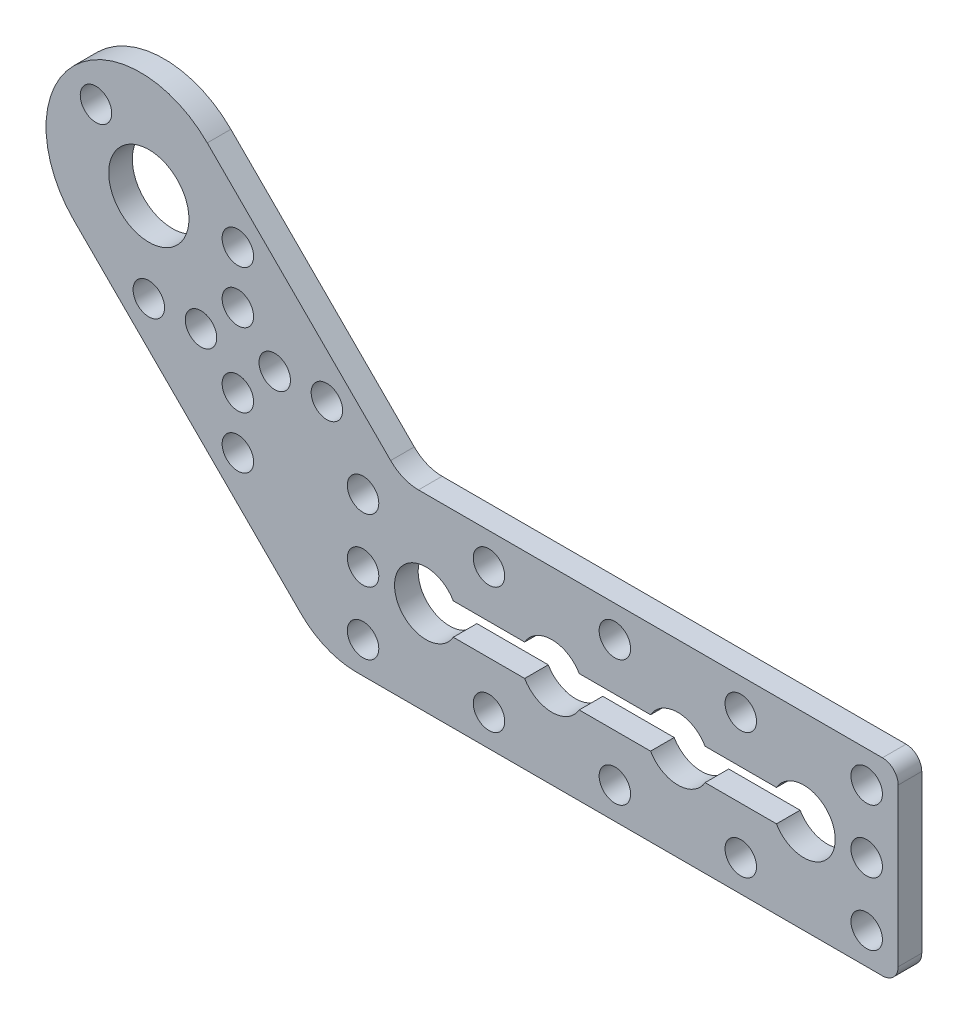
SolidWorks part; units mm, degrees
ref_plane "前视基准面" through (0, 0, 0) normal (0, 0, 1) x (1, 0, 0)
ref_plane "上视基准面" through (0, 0, 0) normal (0, 1, 0) x (1, 0, 0)
ref_plane "右视基准面" through (0, 0, 0) normal (1, 0, 0) x (0, 0, -1)
sketch "草图1" plane through (0, 0, 0) normal (0, 0, 1) x (1, 0, 0)
  line L0 (0, 0) -> (35.0294, 0)
  line L1 (-9.9411, -24) -> (0, 0)
  line L2 (35.0294, -24) -> (-9.9411, -24)
  line L3 (-9.9411, -24) -> (-38.2254, 4.2843) construction
  line L4 (35.0294, -12) -> (-4.9706, -12) construction
  line L5 (-21.2548, 21.2548) -> (0, 0) construction
  arc A0 (-21.2548, 21.2548) -> (-38.2254, 4.2843) centre (-29.7401, 12.7696) ccw construction
  arc A1 (35.0294, -24) -> (35.0294, 0) centre (35.0294, -12) ccw
  circle A2 centre (35.0294, -12) radius 4
  dimension "D6" = 8
  dimension "D1" = 135
  dimension "D2" = 40
  dimension "D3" = 40
  dimension "D4" = 24
  dimension "D5" = 24
extrude "凸台-拉伸1" add sketch "草图1" along normal blind 3
sketch "草图2" plane through (0, 0, 3) normal (0, 0, 1) x (1, 0, 0)
  line L0 (35.0294, -12) -> (43.0294, -12) construction
  circle A0 centre (43.0294, -12) radius 2
  dimension "D1" = 4
  dimension "D2" = 8
extrude "切除-拉伸1" cut sketch "草图2" against normal blind 3
pattern_circular "阵列(圆周)1" count 8 over 360 about axis through (35.0294, -12, 0) along (0, 0, 1) of "切除-拉伸1"
sketch "草图3" plane through (0, 0, 3) normal (0, 0, 1) x (1, 0, 0)
  line L0 (19.0294, -4) -> (35.0294, -4) construction
  line L1 (19.0294, -20) -> (35.0294, -20) construction
  line L2 (19.0294, -20) -> (19.0294, -4) construction
  circle A0 centre (19.0294, -4) radius 2
  circle A1 centre (19.0294, -20) radius 2
  circle A2 centre (19.0294, -12) radius 2
  dimension "D2" = 4
  dimension "D1" = 16
extrude "切除-拉伸2" cut sketch "草图3" against normal blind 3
pattern_linear "阵列(线性)1" count 3 spacing 8 along (-1, 0, 0) of "切除-拉伸2"
sketch "草图4" plane through (0, 0, 3) normal (0, 0, 1) x (1, 0, 0)
  line L0 (27.0294, -4) -> (35.0294, -4) construction
  line L1 (27.0294, -20) -> (35.0294, -20) construction
  circle A0 centre (27.0294, -4) radius 2
  circle A1 centre (27.0294, -20) radius 2
  circle A2 centre (29.3726, -17.6569) radius 2 construction
  dimension "D1" = 8
sketch "草图8" plane through (0, 0, 3) normal (0, 0, 1) x (1, 0, 0)
  line L0 (19.0294, -10) -> (-7.5153, -10)
  line L1 (19.0294, -14) -> (-11.2342, -14)
  line L2 (-11.2342, -14) -> (-7.5153, -10)
  circle A0 centre (19.0294, -12) radius 2 construction
  circle A1 centre (3.0294, -12) radius 2 construction
  arc A2 (19.0294, -14) -> (19.0294, -10) centre (19.0294, -12) ccw
sketch "草图14" plane through (0, 0, 3) normal (0, 0, 1) x (1, 0, 0)
  line L0 (3.0294, -10) -> (19.0294, -10)
  line L1 (3.0294, -14) -> (19.0294, -14)
  line L2 (19.0294, -14) -> (19.0294, -10)
  line L3 (3.0294, -10) -> (3.0294, -14)
  circle A0 centre (3.0294, -12) radius 2 construction
  circle A1 centre (19.0294, -12) radius 2 construction
extrude "切除-拉伸6" cut sketch "草图14" against normal blind 3
sketch "草图16" plane through (0, 0, 3) normal (0, 0, 1) x (1, 0, 0)
  line L0 (-4.9706, -20) -> (3.0294, -20) construction
  circle A0 centre (-4.9706, -20) radius 2
  circle A1 centre (3.0294, -20) radius 2 construction
  dimension "D1" = 8
extrude "切除-拉伸7" [suppressed] cut sketch "草图16" against normal blind 3
sketch "草图31" plane through (0, 0, 3) normal (0, 0, 1) x (1, 0, 0)
  line L0 (7.7157, -8.6863) -> (19.0294, -20) construction
  line L1 (-9.9411, -24) -> (35.0294, -24) construction
  line L2 (35.0294, -12) -> (-9.2377, -12) construction
  circle A0 centre (7.7157, -8.6863) radius 2
  circle A1 centre (11.0294, -4) radius 2 construction
  dimension "D1" = 16
  dimension "D2" = 45
extrude "切除-拉伸9" [suppressed] cut sketch "草图31" against normal blind 3
sketch "草图33" plane through (0, 0, 3) normal (0, 0, 1) x (1, 0, 0)
  line L0 (7.7157, -15.3137) -> (19.0294, -4) construction
  line L1 (-9.9411, -24) -> (35.0294, -24) construction
  circle A0 centre (7.7157, -15.3137) radius 2
  circle A1 centre (3.0294, -20) radius 2 construction
  dimension "D1" = 45
  dimension "D2" = 16
extrude "切除-拉伸11" [suppressed] cut sketch "草图33" against normal blind 3 contours A0
fillet "圆角6" [suppressed] radius 0.2
sketch "草图36" plane through (0, 0, 3) normal (0, 0, 1) x (1, 0, 0)
  line L0 (0.6837, -6.3405) -> (-10.63, 4.9732) construction
  line L1 (35.0294, 0) -> (0, 0) construction
  line L2 (0, 0) -> (-12.775, 12.775) construction
  line L3 (11.0294, -4) -> (-1.6569, -4) construction
  circle A0 centre (0.6837, -6.3405) radius 2
  circle A1 centre (3.0294, -4) radius 2 construction
  dimension "D2" = 4
  dimension "D1" = 135
  dimension "D3" = 12.69
  dimension "D4" = 16
extrude "切除-拉伸12" [suppressed] cut sketch "草图36" against normal blind 3
fillet "圆角8" [suppressed] radius 0.2
sketch "草图39" plane through (0, 0, 3) normal (0, 0, 1) x (1, 0, 0)
  line L0 (7.7157, -8.6863) -> (19.0294, -20) construction
  line L1 (-9.9411, -24) -> (35.0294, -24) construction
  circle A0 centre (7.7157, -8.6863) radius 2
  circle A1 centre (11.0294, -4) radius 2 construction
  dimension "D2" = 16
  dimension "D1" = 45
extrude "切除-拉伸13" [suppressed] cut sketch "草图39" against normal blind 25.4
sketch "草图40" plane through (0, 0, 3) normal (0, 0, 1) x (1, 0, 0)
  line L0 (7.7157, -15.3137) -> (19.0294, -4) construction
  line L1 (-9.9411, -24) -> (35.0294, -24) construction
  circle A0 centre (7.7157, -15.3137) radius 2
  circle A1 centre (3.0294, -20) radius 2 construction
  dimension "D1" = 45
  dimension "D2" = 16
extrude "切除-拉伸14" [suppressed] cut sketch "草图40" against normal blind 25.4
fillet "圆角9" [suppressed] radius 0.2
sketch "草图42" plane through (0, 0, 3) normal (0, 0, 1) x (1, 0, 0)
  line L0 (-0.2843, -8.6863) -> (11.0294, -20) construction
  line L1 (-9.9411, -24) -> (35.0294, -24) construction
  line L2 (-0.2843, -15.3137) -> (11.0294, -4) construction
  circle A0 centre (-0.2843, -8.6863) radius 2
  circle A1 centre (3.0294, -4) radius 2 construction
  circle A3 centre (-0.2843, -15.3137) radius 2
  dimension "D1" = 45
  dimension "D2" = 16
  dimension "D3" = 45
  dimension "D4" = 16
extrude "切除-拉伸15" [suppressed] cut sketch "草图42" against normal blind 25.4
sketch "草图43" [suppressed] plane through (0, 0, 3) normal (0, 0, 1) x (1, 0, 0)
  line L0 (-1.6985, -10.1005) -> (0.201, -12)
  line L1 (3.2579, -11.178) -> (4.1469, -10.289)
  line L2 (4.1469, -10.289) -> (1.1299, -7.2721)
  line L3 (-0.2843, -8.6863) -> (11.0294, -20) construction
  line L4 (-0.375, -15.4044) -> (11.0294, -4) construction
  line L5 (-1.6985, -13.8995) -> (1.1299, -16.7279)
  line L6 (1.1299, -16.7279) -> (5.0318, -12.8261)
  line L7 (5.0318, -12.8261) -> (3.2579, -11.178)
  line L8 (2.0994, -10.1016) -> (1.6152, -10.5858) construction
  line L9 (35.0294, 0) -> (0, 0) construction
  line L10 (0.201, -12) -> (-1.6985, -13.8995)
  line L11 (-1.6985, -10.1005) -> (1.1299, -7.2721)
  circle A0 centre (-0.2843, -8.6863) radius 2 construction
  circle A1 centre (-0.2843, -15.3137) radius 2 construction
  dimension "D1" = 135
extrude "切除-拉伸17" [suppressed] cut sketch "草图43" against normal blind 25.4
fillet "圆角10" [suppressed] radius 0.5
mirror "镜向2" about plane through (-9.9411, -24, 3) normal (0.9239, -0.3827, 0) of bodies 116 110
fillet "圆角1" radius 5 1 edges at (0, 0, 1.5)
fillet "圆角2" radius 10 1 edges at (-9.9411, -24, 1.5)
sketch "草图11" plane through (0, 0, 3) normal (0, 0, 1) x (1, 0, 0)
  line L0 (0, 0) -> (-9.6258, -23.2388) construction
  line L1 (3.0294, -12) -> (-4.9706, -12) construction
  arc A0 (-12.8701, -21.0711) -> (-5.799, -24) centre (-5.799, -14) ccw construction
sketch "草图13" plane through (0, 0, 3) normal (0, 0, 1) x (1, 0, 0)
  circle A0 centre (-4.9706, -12) radius 2
  circle A1 centre (3.0294, -12) radius 2 construction
extrude "切除-拉伸5" cut sketch "草图13" against normal blind 3
sketch "草图44" plane through (0, 0, 3) normal (0, 0, 1) x (1, 0, 0)
  line L0 (35.0294, 0) -> (2.0711, 0) construction
  line L1 (23.7346, 0) -> (71.0294, 0)
  line L2 (23.7346, 0) -> (23.7346, -24)
  line L3 (23.7346, -24) -> (71.0294, -24)
  line L4 (71.0294, 0) -> (71.0294, -24)
  line L5 (-5.799, -24) -> (35.0294, -24) construction
  line L6 (43.0294, -12) -> (71.0294, -12) construction
  dimension "D1" = 28
extrude "凸台-拉伸2" add sketch "草图44" against normal up to surface (3 mm away) up to face at (-2.9706, -12, 0)
sketch "草图45" plane through (0, 0, 3) normal (0, 0, 1) x (1, 0, 0)
  line L0 (67.0294, -4) -> (19.0294, -4) construction
  line L1 (71.0294, -24) -> (71.0294, 0) construction
  circle A0 centre (67.0294, -4) radius 2
  circle A1 centre (67.0294, -20) radius 2
  dimension "D1" = 4
  dimension "D2" = 16
  dimension "D3" = 4
extrude "切除-拉伸18" cut sketch "草图45" against normal blind 10
pattern_linear "阵列(线性)2" count 6 spacing 8 along (-1, 0, 0) of "切除-拉伸18"
sketch "草图47" plane through (0, 0, 3) normal (0, 0, 1) x (1, 0, 0)
  line L0 (67.0294, -12) -> (67.0294, -20) construction
  line L1 (67.0294, -12) -> (19.0294, -12) construction
  line L2 (59.0294, -10) -> (35.0294, -10)
  line L3 (19.0294, -10) -> (3.0294, -10) construction
  line L4 (17.0627, -10) -> (17.0627, -14)
  line L5 (3.0294, -14) -> (19.0294, -14) construction
  line L6 (35.0294, -14) -> (59.0294, -14)
  line L8 (35.0294, -12) -> (35.0294, -4) construction
  line L9 (27.0294, -12) -> (27.0294, -4) construction
  line L10 (17.0627, -10) -> (27.0294, -10)
  line L11 (17.0627, -14) -> (27.0294, -14)
  line L12 (59.0294, -10) -> (59.0294, -4) construction
  circle A0 centre (67.0294, -12) radius 2
  circle A2 centre (67.0294, -4) radius 2 construction
  arc A3 (35.0294, -10) -> (35.0294, -14) centre (35.0294, -12) ccw
  arc A4 (27.0294, -14) -> (27.0294, -10) centre (27.0294, -12) ccw
  circle A5 centre (27.0294, -4) radius 2 construction
  arc A6 (59.0294, -14) -> (59.0294, -10) centre (59.0294, -12) ccw
  dimension "D1" = 2
  dimension "D2" = 2
extrude "切除-拉伸19" cut sketch "草图47" against normal blind 10
fillet "圆角11" radius 2 2 edges at (71.0294, -24, 1.5) (71.0294, 0, 1.5)
sketch "草图48" plane through (0, 0, 3) normal (0, 0, 1) x (1, 0, 0)
  line L0 (-10.6274, -17.6569) -> (-16.2843, -12) construction
  line L1 (-12.8701, -21.0711) -> (-41.7401, 7.799) construction
  line L2 (-4.9706, -20) -> (3.0294, -20) construction
  circle A0 centre (-4.9706, -20) radius 2
  circle A1 centre (3.0294, -20) radius 2 construction
  circle A2 centre (-10.6274, -17.6569) radius 2
  dimension "D1" = 8
  dimension "D2" = 8
extrude "切除-拉伸20" cut sketch "草图48" against normal blind 10
sketch "草图49" plane through (0, 0, 3) normal (0, 0, 1) x (1, 0, 0)
  line L0 (-33.7407, 2.2965) -> (-11.1397, -21.4851)
  line L1 (-11.1397, -21.4851) -> (-6.8616, -17.4194)
  line L2 (-6.8616, -17.4194) -> (-11.8728, -12.1464)
  line L3 (-11.8728, -12.1464) -> (-1.3201, -0.8589)
  line L4 (-1.3201, -0.8589) -> (-18.0661, 15.5538)
  line L5 (-18.0661, 15.5538) -> (-33.7407, 2.2965)
extrude "凸台-拉伸3" [suppressed] add sketch "草图49" against normal up to surface (3 mm away)
sketch "草图50" plane through (0, 0, 3) normal (0, 0, 1) x (1, 0, 0)
  line L0 (-25.2548, 0.2843) -> (-25.2548, 16.2843) construction
  line L1 (-25.2548, 16.2843) -> (-17.2548, 8.2843) construction
  line L2 (-24.7696, 24.7696) -> (-1.4645, 1.4645) construction
  line L3 (-17.2548, 8.2843) -> (-17.2548, -7.7157) construction
  line L4 (-17.2548, 8.2843) -> (-9.2548, 0.2843) construction
  line L5 (-9.2548, -15.7157) -> (-9.2548, 0.2843) construction
  circle A0 centre (-25.2548, 0.2843) radius 2
  circle A1 centre (-27.598, 10.6274) radius 2 construction
  circle A2 centre (-17.2548, 8.2843) radius 2
  circle A3 centre (-17.2548, -7.7157) radius 2
  circle A4 centre (-9.2548, 0.2843) radius 2 construction
  circle A5 centre (-9.2548, -15.7157) radius 2 construction
  dimension "D1" = 16
  dimension "D2" = 8
  dimension "D3" = 16
  dimension "D4" = 16
  dimension "D5" = 8
extrude "切除-拉伸21" [suppressed] cut sketch "草图50" against normal blind 10
sketch "草图52" [suppressed] plane through (0, 0, 3) normal (0, 0, 1) x (1, 0, 0)
  line L0 (-16.2843, -0.6863) -> (-27.598, 10.6274) construction
  line L1 (-12.8701, -21.0711) -> (-41.7401, 7.799) construction
  circle A0 centre (-16.2843, -0.6863) radius 2
  circle A1 centre (-17.2548, -7.7157) radius 2 construction
  dimension "D1" = 16
extrude "切除-拉伸22" [suppressed] cut sketch "草图52" against normal blind 10
sketch "草图53" plane through (0, 0, 3) normal (0, 0, 1) x (1, 0, 0)
  line L0 (-4.9706, -4) -> (3.0294, -4) construction
  line L2 (-4.9706, -4) -> (-4.9706, -12) construction
  circle A0 centre (-4.9706, -4) radius 2
  circle A1 centre (3.0294, -4) radius 2 construction
extrude "切除-拉伸23" [suppressed] cut sketch "草图53" against normal blind 10
sketch "草图58" [suppressed] plane through (0, 0, 3) normal (0, 0, 1) x (1, 0, 0)
  line L0 (-12.9706, -12) -> (-4.9706, -12) construction
  circle A0 centre (-12.9706, -12) radius 2
  circle A1 centre (-4.9706, -12) radius 2 construction
  circle A2 centre (-17.2548, -7.7157) radius 2 construction
  circle A3 centre (-12.9706, 4) radius 2
  circle A4 centre (-17.2548, 8.2843) radius 2 construction
  dimension "D1" = 8
  dimension "D2" = 16
extrude "切除-拉伸24" [suppressed] cut sketch "草图58" against normal blind 10
sketch "草图61" [suppressed] plane through (0, 0, 3) normal (0, 0, 1) x (1, 0, 0)
  line L0 (-27.598, 10.6274) -> (-4.9706, -12) construction
  line L1 (-23.3553, 3.5563) -> (-12.0416, -7.7574)
  line L2 (-9.2132, -4.9289) -> (-20.5269, 6.3848)
  arc A0 (-20.5269, 6.3848) -> (-23.3553, 3.5563) centre (-21.9411, 4.9706) ccw
  circle A1 centre (-27.598, 10.6274) radius 2 construction
  arc A2 (-12.0416, -7.7574) -> (-9.2132, -4.9289) centre (-10.6274, -6.3431) ccw
  circle A3 centre (-4.9706, -4) radius 2 construction
  dimension "D1" = 8
  dimension "D2" = 8
extrude "切除-拉伸25" [suppressed] cut sketch "草图61" against normal blind 10
sketch "草图62" plane through (0, 0, 3) normal (0, 0, 1) x (1, 0, 0)
  line L0 (-25.2548, 16.2843) -> (-21.2548, 12.2843) construction
  line L1 (-24.7696, 24.7696) -> (-1.4645, 1.4645) construction
  circle A0 centre (-21.2548, 12.2843) radius 2
  circle A1 centre (-25.2548, 16.2843) radius 2 construction
  circle A2 centre (-21.2548, -3.7157) radius 2
  dimension "D1" = 4
  dimension "D2" = 16
extrude "切除-拉伸26" [suppressed] cut sketch "草图62" against normal blind 10
sketch "草图63" plane through (0, 0, 3) normal (0, 0, 1) x (1, 0, 0)
  circle A0 centre (-4.9706, -0.6863) radius 3.0171
extrude "凸台-拉伸4" [suppressed] add sketch "草图63" against normal up to surface (3 mm away)
sketch "草图64" plane through (0, 0, 3) normal (0, 0, 1) x (1, 0, 0)
  line L0 (-4.9706, -4) -> (3.0294, -4) construction
  circle A0 centre (-4.9706, -4) radius 2
  circle A1 centre (3.0294, -4) radius 2 construction
  dimension "D1" = 8
extrude "切除-拉伸27" [suppressed] cut sketch "草图64" against normal blind 10
sketch "草图65" plane through (0, 0, 3) normal (0, 0, 1) x (1, 0, 0)
  circle A0 centre (-10.6274, -17.6569) radius 3.287
extrude "凸台-拉伸5" [suppressed] add sketch "草图65" against normal up to surface (3 mm away)
sketch "草图66" plane through (0, 0, 3) normal (0, 0, 1) x (1, 0, 0)
  circle A0 centre (-27.3986, 0) radius 3.2271
extrude "凸台-拉伸6" add sketch "草图66" against normal up to surface (3 mm away) up to face at (-8.6274, -17.6569, 0)
sketch "草图67" plane through (0, 0, 3) normal (0, 0, 1) x (1, 0, 0)
  line L0 (-25.2548, 0.2843) -> (-25.2548, 16.2843) construction
  circle A0 centre (-25.2548, 0.2843) radius 2
  circle A1 centre (-25.2548, 16.2843) radius 2 construction
  dimension "D1" = 16
extrude "切除-拉伸28" cut sketch "草图67" against normal blind 10
sketch "草图70" plane through (0, 0, 3) normal (0, 0, 1) x (1, 0, 0)
  line L0 (-30.5968, 0) -> (-25.3159, -7.2115)
  line L1 (-25.3159, -7.2115) -> (-15.1515, -16.5242)
  line L2 (-15.1515, -16.5242) -> (-1.2744, -1.3778)
  line L3 (-1.2744, -1.3778) -> (-7.2794, 5.9965)
  line L4 (-7.2794, 5.9965) -> (-16.5461, 14.4867)
  line L7 (-30.5968, 0) -> (-16.5461, 14.4867)
extrude "凸台-拉伸7" add sketch "草图70" against normal up to surface (3 mm away) up to face at (-23.2548, 0.2843, 0)
sketch "草图71" plane through (0, 0, 3) normal (0, 0, 1) x (1, 0, 0)
  circle A0 centre (-10.6274, -17.6569) radius 2.8967
extrude "凸台-拉伸8" add sketch "草图71" against normal up to surface (3 mm away) up to face at (-8.6274, -17.6569, 0)
sketch "草图75" plane through (0, 0, 3) normal (0, 0, 1) x (1, 0, 0)
  line L0 (-25.2548, 16.2843) -> (-25.2548, 0.2843) construction
  line L1 (-25.2548, 0.2843) -> (-9.2548, 0.2843) construction
  line L2 (-10.6274, 4.9706) -> (-21.9411, -6.3431) construction
  line L3 (-38.9117, 10.6274) -> (-27.598, 21.9411) construction
  line L4 (-16.2843, -0.6863) -> (-33.2548, 16.2843) construction
  line L5 (-12.8701, -21.0711) -> (-41.7401, 7.799) construction
  line L6 (-21.9411, 16.2843) -> (-10.6274, 4.9706) construction
  line L7 (-24.7696, 24.7696) -> (-1.4645, 1.4645) construction
  circle A0 centre (-25.2548, 0.2843) radius 2
  circle A1 centre (-9.2548, 0.2843) radius 2
  circle A2 centre (-25.2548, 16.2843) radius 2 construction
  circle A3 centre (-21.9411, -6.3431) radius 2
  circle A4 centre (-10.6274, 4.9706) radius 2
  circle A6 centre (-21.9411, 16.2843) radius 2
  circle A7 centre (-17.2548, 8.2843) radius 2
  dimension "D1" = 16
  dimension "D2" = 16
  dimension "D3" = 24
  dimension "D4" = 16
  dimension "D5" = 16
sketch "草图77" plane through (0, 0, 3) normal (0, 0, 1) x (1, 0, 0)
  line L0 (-10.6274, 4.9706) -> (-21.9411, -6.3431) construction
  circle A0 centre (-16.2843, -0.6863) radius 2
  circle A1 centre (-33.2548, 8.2843) radius 2 construction
extrude "切除-拉伸31" cut sketch "草图77" against normal blind 10
sketch "草图78" plane through (0, 0, 3) normal (0, 0, 1) x (1, 0, 0)
  line L0 (-16.2843, -0.6863) -> (-33.2548, 16.2843) construction
  circle A0 centre (-21.9411, 4.9706) radius 2
  circle A1 centre (-27.598, 10.6274) radius 2 construction
  circle A2 centre (-16.2843, -0.6863) radius 2 construction
  dimension "D1" = 8
extrude "切除-拉伸32" cut sketch "草图78" against normal blind 10
sketch "草图79" plane through (0, 0, 3) normal (0, 0, 1) x (1, 0, 0)
  line L0 (-10.6274, -6.3431) -> (-16.2843, -0.6863) construction
  line L1 (-16.2843, -0.6863) -> (-33.2548, 16.2843) construction
  circle A0 centre (-10.6274, -6.3431) radius 2
  circle A1 centre (-21.9411, 4.9706) radius 2 construction
  dimension "D1" = 8
extrude "切除-拉伸33" cut sketch "草图79" against normal blind 10
ref_plane "基准面1" through (-8.4853, -8.4853, 0) normal (-0.7071, -0.7071, 0) x (0, 0, 1)
sketch "草图80" plane through (0, 0, 3) normal (0, 0, 1) x (1, 0, 0)
  line L0 (-25.2548, 0.2843) -> (-9.2548, 0.2843) construction
  line L1 (-17.2548, -7.7157) -> (-17.2548, 8.2843) construction
  line L2 (-17.2548, 0.2843) -> (-33.2548, 16.2843) construction
  line L3 (69.0294, 0) -> (2.0711, 0) construction
  line L4 (-21.9411, -6.3431) -> (-38.9117, 10.6274) construction
  line L5 (-12.8701, -21.0711) -> (-41.7401, 7.799) construction
  line L6 (-10.6274, 4.9706) -> (-27.598, 21.9411) construction
  line L7 (-10.6274, -17.6569) -> (-21.9411, -6.3431) construction
  line L8 (-24.7696, 24.7696) -> (-1.4645, 1.4645) construction
  line L9 (-21.9411, -6.3431) -> (-10.6274, 4.9706) construction
  line L10 (-29.9411, 4.9706) -> (-41.2548, 16.2843) construction
  circle A0 centre (-25.2548, 0.2843) radius 2
  circle A1 centre (-33.2548, 8.2843) radius 2 construction
  circle A2 centre (-27.598, 10.6274) radius 2 construction
  circle A3 centre (-25.2548, 16.2843) radius 2 construction
  circle A4 centre (-27.598, 21.9411) radius 2 construction
  circle A5 centre (-33.2548, 24.2843) radius 2 construction
  circle A6 centre (-33.2548, 16.2843) radius 4 construction
  circle A7 centre (-38.9117, 21.9411) radius 2 construction
  circle A8 centre (-41.2548, 16.2843) radius 2 construction
  circle A9 centre (-38.9117, 10.6274) radius 2 construction
  circle A10 centre (-33.2548, 8.2843) radius 2
  circle A11 centre (-27.598, 10.6274) radius 2
  circle A12 centre (-25.2548, 16.2843) radius 2
  circle A13 centre (-27.598, 21.9411) radius 2
  circle A14 centre (-33.2548, 24.2843) radius 2
  circle A15 centre (-33.2548, 16.2843) radius 4
  circle A16 centre (-38.9117, 21.9411) radius 2
  circle A17 centre (-41.2548, 16.2843) radius 2
  circle A18 centre (-38.9117, 10.6274) radius 2
  circle A19 centre (-17.2548, 8.2843) radius 2
  circle A20 centre (-9.2548, 0.2843) radius 2
  circle A21 centre (-17.2548, -7.7157) radius 2
  circle A22 centre (-21.9411, -6.3431) radius 2
  circle A23 centre (-10.6274, 4.9706) radius 2
  circle A24 centre (-30.4264, 2.1421) radius 2 construction
  circle A25 centre (-19.1127, 13.4558) radius 2 construction
  circle A26 centre (-10.6274, -17.6569) radius 2
  dimension "D6" = 8
  dimension "D8" = 16
  dimension "D9" = 16
  dimension "D1" = 16
  dimension "D2" = 16
  dimension "D3" = 16
  dimension "D4" = 8
  dimension "D5" = 135
  dimension "D7" = 24
extrude "切除-拉伸34" cut sketch "草图80" against normal blind 10
sketch "草图81" plane through (0, 0, 3) normal (0, 0, 1) x (1, 0, 0)
  line L0 (-23.3553, 3.5563) -> (-12.0416, -7.7574)
  line L1 (-20.5269, 6.3848) -> (-9.2132, -4.9289)
  circle A0 centre (-21.9411, 4.9706) radius 2 construction
  circle A1 centre (-10.6274, -6.3431) radius 2 construction
  arc A2 (-12.0416, -7.7574) -> (-9.2132, -4.9289) centre (-10.6274, -6.3431) ccw
  arc A3 (-20.5269, 6.3848) -> (-23.3553, 3.5563) centre (-21.9411, 4.9706) ccw
extrude "切除-拉伸35" cut sketch "草图81" against normal blind 10
sketch "草图82" plane through (0, 0, 3) normal (0, 0, 1) x (1, 0, 0)
  line L2 (-9.2132, -4.9289) -> (-20.5269, 6.3848)
  line L3 (-23.3553, 3.5563) -> (-12.0416, -7.7574)
  line L4 (-9.2132, -4.9289) -> (-20.5269, 6.3848)
  line L5 (-23.3553, 3.5563) -> (-12.0416, -7.7574)
  line L6 (27.0294, -10) -> (3.0294, -10)
  line L7 (3.0294, -14) -> (27.0294, -14)
  line L8 (27.0294, -10) -> (3.0294, -10)
  line L9 (3.0294, -14) -> (27.0294, -14)
  line L10 (59.0294, -10) -> (35.0294, -10)
  line L11 (35.0294, -14) -> (59.0294, -14)
  line L12 (59.0294, -10) -> (35.0294, -10)
  line L13 (35.0294, -14) -> (59.0294, -14)
  circle A0 centre (67.0294, -4) radius 2 construction
  circle A1 centre (67.0294, -4) radius 2
  circle A2 centre (67.0294, -12) radius 2 construction
  circle A3 centre (67.0294, -12) radius 2
  circle A4 centre (67.0294, -20) radius 2 construction
  circle A5 centre (67.0294, -20) radius 2
  circle A7 centre (-27.598, 21.9411) radius 2 construction
  circle A8 centre (51.0294, -20) radius 2 construction
  circle A9 centre (51.0294, -20) radius 2
  circle A11 centre (-38.9117, 10.6274) radius 2 construction
  circle A12 centre (51.0294, -4) radius 2 construction
  circle A13 centre (51.0294, -4) radius 2
  circle A14 centre (35.0294, -4) radius 2 construction
  circle A15 centre (35.0294, -4) radius 2
  circle A16 centre (35.0294, -20) radius 2 construction
  circle A17 centre (35.0294, -20) radius 2
  circle A18 centre (27.0294, -20) radius 2 construction
  circle A19 centre (27.0294, -20) radius 2
  circle A20 centre (27.0294, -4) radius 2 construction
  circle A21 centre (27.0294, -4) radius 2
  circle A22 centre (19.0294, -4) radius 2 construction
  circle A23 centre (19.0294, -4) radius 2
  circle A24 centre (19.0294, -20) radius 2 construction
  circle A25 centre (19.0294, -20) radius 2
  circle A26 centre (11.0294, -20) radius 2 construction
  circle A27 centre (11.0294, -20) radius 2
  circle A28 centre (3.0294, -20) radius 2 construction
  circle A29 centre (3.0294, -20) radius 2
  circle A30 centre (-4.9706, -20) radius 2 construction
  circle A31 centre (-4.9706, -20) radius 2
  circle A32 centre (-10.6274, -17.6569) radius 2 construction
  circle A33 centre (-10.6274, -17.6569) radius 2
  circle A34 centre (3.0294, -4) radius 2 construction
  circle A35 centre (3.0294, -4) radius 2
  circle A36 centre (11.0294, -4) radius 2 construction
  circle A37 centre (11.0294, -4) radius 2
  circle A38 centre (-33.2548, 24.2843) radius 2 construction
  circle A39 centre (-33.2548, 24.2843) radius 2
  circle A40 centre (-41.2548, 16.2843) radius 2 construction
  circle A41 centre (-41.2548, 16.2843) radius 2
  circle A42 centre (-33.2548, 16.2843) radius 4 construction
  circle A43 centre (-33.2548, 16.2843) radius 4
  circle A44 centre (-33.2548, 8.2843) radius 2 construction
  circle A45 centre (-33.2548, 8.2843) radius 2
  circle A46 centre (-27.598, 10.6274) radius 2 construction
  circle A47 centre (-27.598, 10.6274) radius 2
  circle A48 centre (-25.2548, 16.2843) radius 2 construction
  circle A49 centre (-25.2548, 16.2843) radius 2
  circle A50 centre (-25.2548, 0.2843) radius 2 construction
  circle A51 centre (-25.2548, 0.2843) radius 2
  circle A52 centre (-17.2548, 8.2843) radius 2 construction
  circle A53 centre (-17.2548, 8.2843) radius 2
  circle A54 centre (-17.2548, -7.7157) radius 2 construction
  circle A55 centre (-17.2548, -7.7157) radius 2
  circle A56 centre (-9.2548, 0.2843) radius 2 construction
  circle A57 centre (-9.2548, 0.2843) radius 2
  circle A58 centre (-10.6274, 4.9706) radius 2 construction
  circle A59 centre (-10.6274, 4.9706) radius 2
  circle A60 centre (-21.9411, -6.3431) radius 2 construction
  circle A61 centre (-21.9411, -6.3431) radius 2
  circle A62 centre (-27.598, 21.9411) radius 2
  circle A63 centre (-38.9117, 10.6274) radius 2
  arc A64 (-12.0416, -7.7574) -> (-9.2132, -4.9289) centre (-10.6274, -6.3431) ccw
  arc A65 (-20.5269, 6.3848) -> (-23.3553, 3.5563) centre (-21.9411, 4.9706) ccw
  arc A66 (-12.0416, -7.7574) -> (-9.2132, -4.9289) centre (-10.6274, -6.3431) ccw
  arc A67 (-20.5269, 6.3848) -> (-23.3553, 3.5563) centre (-21.9411, 4.9706) ccw
  arc A68 (27.0294, -14) -> (27.0294, -10) centre (27.0294, -12) ccw
  arc A69 (3.0294, -10) -> (3.0294, -14) centre (3.0294, -12) ccw
  arc A70 (27.0294, -14) -> (27.0294, -10) centre (27.0294, -12) ccw
  arc A71 (3.0294, -10) -> (3.0294, -14) centre (3.0294, -12) ccw
  arc A72 (35.0294, -10) -> (35.0294, -14) centre (35.0294, -12) ccw
  arc A73 (59.0294, -14) -> (59.0294, -10) centre (59.0294, -12) ccw
  arc A74 (35.0294, -10) -> (35.0294, -14) centre (35.0294, -12) ccw
  arc A75 (59.0294, -14) -> (59.0294, -10) centre (59.0294, -12) ccw
  dimension "D1" = 0
  dimension "D2" = 0
  dimension "D3" = 0
extrude "凸台-拉伸9" add sketch "草图82" against normal up to surface (3 mm away) up to face at (-8.6274, -17.6569, 0)
sketch "草图84" plane through (0, 0, 3) normal (0, 0, 1) x (1, 0, 0)
  line L0 (-32.1942, 15.2236) -> (-38.9117, 21.9411) construction
  line L1 (-12.8701, -21.0711) -> (-41.7401, 7.799) construction
  line L2 (-20.8805, -7.4038) -> (-37.851, 9.5668) construction
  line L3 (-37.851, 9.5668) -> (-32.1942, 15.2236) construction
  line L4 (-20.8805, -7.4038) -> (-9.5668, 3.9099) construction
  line L5 (-15.2236, -1.747) -> (-32.1942, 15.2236) construction
  circle A0 centre (-32.1942, 15.2236) radius 5.1
  circle A1 centre (-20.8805, -7.4038) radius 2
  circle A2 centre (-9.5668, 3.9099) radius 2
  circle A3 centre (-4.9706, -12) radius 2 construction
  dimension "D1" = 10.2
  dimension "D2" = 9.5
  dimension "D3" = 24
  dimension "D4" = 8
extrude "切除-拉伸36" cut sketch "草图84" against normal blind 10
sketch "草图85" plane through (0, 0, 3) normal (0, 0, 1) x (1, 0, 0)
  line L0 (-27.598, 5.9411) -> (-27.598, 21.9411) construction
  line L1 (-38.9117, 10.6274) -> (-22.9117, 10.6274) construction
  circle A0 centre (-27.598, 5.9411) radius 2
  circle A2 centre (-22.9117, 10.6274) radius 2
  circle A3 centre (-20.8805, -7.4038) radius 2 construction
  dimension "D1" = 16
  dimension "D2" = 16
extrude "切除-拉伸37" [suppressed] cut sketch "草图85" against normal blind 10
sketch "草图88" plane through (0, 0, 3) normal (0, 0, 1) x (1, 0, 0)
  line L1 (63.0294, 4.4281) -> (79.0646, 4.4281)
  line L2 (63.0294, 4.4281) -> (63.0294, -27.701)
  line L3 (63.0294, -27.701) -> (79.0646, -27.701)
  line L4 (79.0646, 4.4281) -> (79.0646, -27.701)
  circle A0 centre (59.0294, -20) radius 2 construction
  dimension "D1" = 4
extrude "切除-拉伸38" cut sketch "草图88" against normal blind 10
fillet "圆角12" radius 2 2 edges at (63.0294, -24, 1.5) (63.0294, 0, 1.5)
sketch "草图89" plane through (0, 0, 3) normal (0, 0, 1) x (1, 0, 0)
  line L0 (-38.9117, 21.9411) -> (-26.5373, 9.5668) construction
  line L1 (-26.5373, 9.5668) -> (-20.8805, 15.2236) construction
  line L2 (-12.8701, -21.0711) -> (-41.7401, 7.799) construction
  circle A0 centre (-38.9117, 21.9411) radius 2 construction
  circle A3 centre (-20.8805, 15.2236) radius 2
  circle A5 centre (-20.8805, -0.7764) radius 2
  dimension "D1" = 16
  dimension "D2" = 17.5
  dimension "D3" = 8
extrude "切除-拉伸39" cut sketch "草图89" against normal blind 3
ref_plane "基准面2" through (-8.4853, -8.4853, 0) normal (-0.7071, -0.7071, 0) x (-0.7071, 0.7071, 0)
mirror "镜向3" about plane through (-8.4853, -8.4853, 0) normal (-0.7071, -0.7071, 0) of "切除-拉伸39"
sketch "草图90" plane through (0, 0, 3) normal (0, 0, 1) x (1, 0, 0)
  line L0 (59.0294, -12) -> (59.0294, -20) construction
  line L1 (59.0294, -12) -> (63.0294, -12) construction
  line L2 (63.0294, -2) -> (63.0294, -22) construction
  circle A0 centre (59.0294, -12) radius 2
  circle A1 centre (59.0294, -20) radius 2 construction
extrude "切除-拉伸40" cut sketch "草图90" against normal blind 10
sketch "草图91" plane through (0, 0, 3) normal (0, 0, 1) x (1, 0, 0)
  line L0 (43.0294, -20) -> (59.0294, -20) construction
  line L1 (51.0294, -20) -> (51.0294, -12) construction
  line L2 (51.0294, -12) -> (63.0294, -12) construction
  line L3 (63.0294, -2) -> (63.0294, -22) construction
  circle A0 centre (51.0294, -12) radius 4
  dimension "D1" = 8
extrude "切除-拉伸41" cut sketch "草图91" against normal blind 10
sketch "草图92" plane through (0, 0, 3) normal (0, 0, 1) x (1, 0, 0)
  line L0 (27.0294, -20) -> (43.0294, -20) construction
  line L1 (27.0294, -4) -> (43.0294, -4) construction
  circle A0 centre (27.0294, -4) radius 2
  circle A1 centre (27.0294, -20) radius 2
  circle A2 centre (43.0294, -4) radius 2 construction
  dimension "D1" = 16
extrude "切除-拉伸42" cut sketch "草图92" against normal blind 10
pattern_linear "阵列(线性)3" count 3 spacing 16 along (-1, 0, 0) of "切除-拉伸42"
pattern_linear "阵列(线性)4" count 4 spacing 16 along (-1, 0, 0) of "切除-拉伸41"
sketch "草图93" plane through (0, 0, 3) normal (0, 0, 1) x (1, 0, 0)
  line L0 (49.5859, -12) -> (59.0294, -12) construction
  line L1 (2.4597, -10) -> (49.5859, -10)
  line L2 (2.4597, -10) -> (2.4597, -14)
  line L3 (2.4597, -14) -> (49.5859, -14)
  line L4 (49.5859, -10) -> (49.5859, -14)
  dimension "D1" = 4
extrude "切除-拉伸43" cut sketch "草图93" against normal blind 10
sketch "草图106" plane through (0, 0, 3) normal (0, 0, 1) x (1, 0, 0)
  line L0 (-23.7089, 6.7383) -> (-32.1942, 15.2236) construction
  line L1 (-12.8701, -21.0711) -> (-41.7401, 7.799) construction
  circle A0 centre (-23.7089, 6.7383) radius 2
  dimension "D1" = 4
  dimension "D2" = 12
extrude "切除-拉伸45" [suppressed] cut sketch "草图106" against normal blind 10
pattern_linear "阵列(线性)5" [suppressed] count 2 spacing 16
sketch "草图107" plane through (0, 0, 3) normal (0, 0, 1) x (1, 0, 0)
  line L0 (-25.5668, 3.9099) -> (-9.5668, 3.9099) construction
  line L2 (-20.8805, 8.5962) -> (-20.8805, -0.7764) construction
  line L3 (-25.5668, 3.9099) -> (-32.1942, 3.9099) construction
  circle A0 centre (-25.5668, 3.9099) radius 2
  circle A1 centre (-20.8805, 8.5962) radius 2
  circle A2 centre (-20.8805, 15.2236) radius 2 construction
  circle A4 centre (-20.8805, -7.4038) radius 2 construction
  dimension "D2" = 16
  dimension "D1" = 16
extrude "切除-拉伸46" cut sketch "草图107" against normal blind 10
